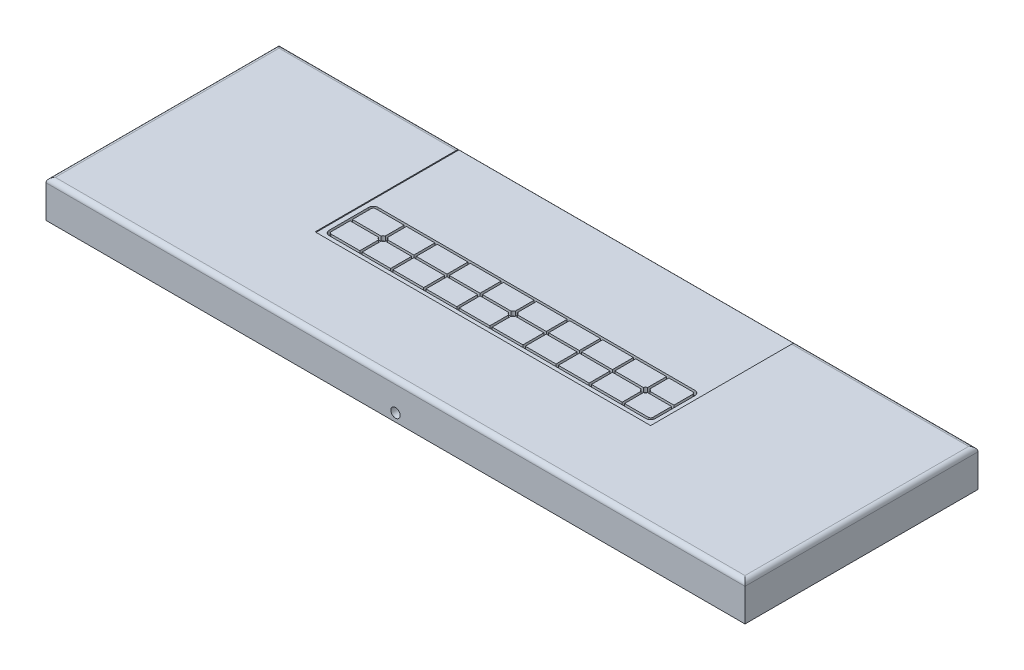
SolidWorks part; units mm, degrees
ref_plane "Front Plane" through (0, 0, 0) normal (0, 0, 1) x (1, 0, 0)
ref_plane "Top Plane" through (0, 0, 0) normal (0, 1, 0) x (1, 0, 0)
ref_plane "Right Plane" through (0, 0, 0) normal (1, 0, 0) x (0, 0, -1)
sketch "Sketch1" plane through (0, 0, 0) normal (0, 1, 0) x (1, 0, 0)
  line L1 (-750, 250) -> (750, 250)
  line L2 (-750, 250) -> (-750, -250)
  line L3 (-750, -250) -> (750, -250)
  line L4 (750, 250) -> (750, -250)
  line L5 (-750, 250) -> (750, -250) construction
  line L6 (-750, -250) -> (750, 250) construction
  point P0 (0, 0)
  dimension "D1" = 1500
  dimension "D2" = 500
extrude "Boss-Extrude1" add sketch "Sketch1" along normal blind 80
fillet "Fillet2" radius 10 4 edges at (0, 80, 250) (-750, 80, 0) (0, 80, -250) (750, 80, 0)
sketch "Sketch3" plane through (0, 0, 0) normal (0, 1, 0) x (1, 0, 0)
  line L0 (740, 148.17) -> (-740, 148.17) construction
  line L3 (-740, -148.17) -> (740, -148.17) construction
  line L4 (740, 240) -> (-740, 240) construction
  line L5 (623.2796, 240) -> (623.2796, -240) construction
  line L6 (-740, -240) -> (740, -240) construction
  dimension "D1" = 296.34
  dimension "D2" = 91.83
  dimension "D3" = 116.7204
sketch "Sketch6" plane through (0, 0, 0) normal (0, 1, 0) x (1, 0, 0)
  line L0 (623.88, 240) -> (623.88, -240) construction
  line L1 (-360, 62.5) -> (360, 62.5)
  line L2 (-360, 62.5) -> (-360, -62.5)
  line L3 (-360, -62.5) -> (360, -62.5)
  line L4 (360, 62.5) -> (360, -62.5)
  line L5 (-360, 62.5) -> (360, -62.5) construction
  line L6 (-360, -62.5) -> (360, 62.5) construction
  line L7 (740, 240) -> (-740, 240) construction
  line L8 (-740, -240) -> (740, -240) construction
  line L9 (740, -240) -> (740, 240) construction
  line L10 (-740, 148.68) -> (740, 148.68) construction
  line L11 (-740, 240) -> (-740, -240) construction
  point P0 (0, 0)
  dimension "D1" = 720
  dimension "D2" = 125
  dimension "D3" = 116.12
  dimension "D4" = 91.32
sketch "Sketch7" plane through (0, 0, 0) normal (0, 1, 0) x (1, 0, 0)
  line L1 (-661.88, 148.17) -> (473.88, 148.17) construction
  line L2 (-661.88, 148.17) -> (-661.88, -148.17) construction
  line L3 (-661.88, -148.17) -> (473.88, -148.17) construction
  line L4 (473.88, 148.17) -> (473.88, -148.17) construction
  line L5 (-661.88, 148.17) -> (473.88, -148.17) construction
  line L6 (-661.88, -148.17) -> (473.88, 148.17) construction
  line L7 (-740, 240) -> (-740, -240) construction
  line L8 (740, -240) -> (740, 240) construction
  line L9 (-661.88, 148.17) -> (-661.88, 308.5509) construction
  line L11 (473.88, 308.5509) -> (473.88, 148.17) construction
  line L12 (-360, -62.5) -> (-360, 376.5169)
  line L13 (360, -62.5) -> (360, 376.5169)
  line L14 (360, 376.5169) -> (-360, 376.5169)
  line L15 (-360, -62.5) -> (360, -62.5)
  point P8 (-94, 0)
  point P9 (-94, 0)
  point P10 (-516.2518, -356.0556)
  dimension "D1" = 78.12
  dimension "D2" = 266.12
  dimension "D3" = 296.34
extrude "Cut-Extrude2" cut sketch "Sketch7" against normal blind 2 from surface at 80 starting at face at (0, 80, 0)
sketch "Sketch5" plane through (0, 0, 0) normal (0, 1, 0) x (1, 0, 0)
  line L0 (-360, 62.5) -> (360, -62.5) construction
  line L6 (-340, 52.5) -> (340, 52.5)
  line L11 (-350, 42.5) -> (-350, -42.5)
  line L12 (-340, -52.5) -> (340, -52.5)
  line L17 (350, 42.5) -> (350, -42.5)
  line L18 (-360, 62.5) -> (-360, -62.5) construction
  line L19 (-360, -62.5) -> (360, -62.5) construction
  line L20 (360, 62.5) -> (360, -62.5) construction
  line L21 (-360, 62.5) -> (360, 62.5) construction
  line L22 (-360, -62.5) -> (360, 62.5) construction
  line L23 (-340, 47.5) -> (-279, 47.5)
  line L24 (-345, 42.5) -> (-345, 2.5)
  line L25 (-340, -47.5) -> (-279, -47.5)
  line L26 (345, 42.5) -> (345, 2.5)
  line L27 (2.5, -52.5) -> (2.5, -18.1303) construction
  line L28 (-350, 0) -> (350, 0) construction
  line L29 (-142, -2.5) -> (-142, -47.5)
  line L30 (0, 47.5) -> (0, 7.0711)
  line L31 (5, 47.5) -> (5, 7.0711)
  line L32 (-71, 47.5) -> (-71, 2.5)
  line L33 (-66, 47.5) -> (-66, 2.5)
  line L34 (142, 47.5) -> (142, 2.5)
  line L35 (147, 47.5) -> (147, 2.5)
  line L36 (71, 47.5) -> (71, 2.5)
  line L37 (76, 47.5) -> (76, 2.5)
  line L38 (213, 47.5) -> (213, 2.5)
  line L39 (218, 47.5) -> (218, 2.5)
  line L40 (284, 47.5) -> (284, 7.0711)
  line L41 (289, 47.5) -> (289, 7.0711)
  line L42 (-142, 47.5) -> (-142, 2.5)
  line L43 (-137, 47.5) -> (-137, 2.5)
  line L44 (-213, 47.5) -> (-213, 2.5)
  line L45 (-208, 47.5) -> (-208, 2.5)
  line L46 (-279, 47.5) -> (-279, 7.0711)
  line L47 (-274, 47.5) -> (-274, 7.0711)
  line L48 (-345, -2.5) -> (-283.5711, -2.5)
  line L49 (-345, 2.5) -> (-283.5711, 2.5)
  line L50 (-279, -7.0711) -> (-279, -47.5)
  line L51 (-274, -7.0711) -> (-274, -47.5)
  line L52 (-137, -2.5) -> (-71, -2.5)
  line L53 (-269.4289, -2.5) -> (-213, -2.5)
  line L54 (-269.4289, 2.5) -> (-213, 2.5)
  line L55 (-213, -2.5) -> (-213, -47.5)
  line L56 (-208, -2.5) -> (-208, -47.5)
  line L57 (-208, -2.5) -> (-142, -2.5)
  line L58 (-137, 2.5) -> (-71, 2.5)
  line L59 (-137, -2.5) -> (-137, -47.5)
  line L60 (-208, 2.5) -> (-142, 2.5)
  line L61 (-66, -2.5) -> (-4.5711, -2.5)
  line L62 (-66, 2.5) -> (-4.5711, 2.5)
  line L63 (-66, -2.5) -> (-66, -47.5)
  line L64 (-71, -2.5) -> (-71, -47.5)
  line L65 (0, -7.0711) -> (0, -47.5)
  line L66 (5, -7.0711) -> (5, -47.5)
  line L67 (9.5711, 2.5) -> (71, 2.5)
  line L68 (9.5711, -2.5) -> (71, -2.5)
  line L69 (76, -2.5) -> (142, -2.5)
  line L70 (76, -2.5) -> (76, -47.5)
  line L71 (71, -2.5) -> (71, -47.5)
  line L72 (76, 2.5) -> (142, 2.5)
  line L73 (142, -2.5) -> (142, -47.5)
  line L74 (147, -2.5) -> (147, -47.5)
  line L75 (147, -2.5) -> (213, -2.5)
  line L76 (147, 2.5) -> (213, 2.5)
  line L77 (213, -2.5) -> (213, -47.5)
  line L78 (218, -2.5) -> (218, -47.5)
  line L79 (218, 2.5) -> (279.4289, 2.5)
  line L80 (218, -2.5) -> (279.4289, -2.5)
  line L81 (284, -7.0711) -> (284, -47.5)
  line L82 (289, -7.0711) -> (289, -47.5)
  line L83 (293.5711, -2.5) -> (345, -2.5)
  line L84 (293.5711, 2.5) -> (345, 2.5)
  line L85 (345, -2.5) -> (345, -42.5)
  line L86 (-345, -2.5) -> (-345, -42.5)
  line L87 (-208, 47.5) -> (-142, 47.5)
  line L88 (-360, 84.24) -> (360, 84.24) construction
  line L89 (289, 47.5) -> (340, 47.5)
  line L90 (218, 47.5) -> (284, 47.5)
  line L91 (76, 47.5) -> (142, 47.5)
  line L92 (147, 47.5) -> (213, 47.5)
  line L93 (-66, 47.5) -> (0, 47.5)
  line L94 (5, 47.5) -> (71, 47.5)
  line L95 (-137, 47.5) -> (-71, 47.5)
  line L96 (-274, 47.5) -> (-213, 47.5)
  line L97 (-274, -47.5) -> (-213, -47.5)
  line L98 (-208, -47.5) -> (-142, -47.5)
  line L99 (-137, -47.5) -> (-71, -47.5)
  line L100 (-66, -47.5) -> (0, -47.5)
  line L101 (5, -47.5) -> (71, -47.5)
  line L102 (76, -47.5) -> (142, -47.5)
  line L103 (147, -47.5) -> (213, -47.5)
  line L104 (218, -47.5) -> (284, -47.5)
  line L105 (289, -47.5) -> (340, -47.5)
  line L106 (-279, 7.0711) -> (-274, -7.0711) construction
  line L107 (-274, 7.0711) -> (-279, -7.0711) construction
  line L108 (-360, -62.5) -> (-360, 246) construction
  line L109 (360, 246) -> (360, -62.5) construction
  line L110 (-740, 148.68) -> (740, 148.68) construction
  arc A0 (-340, -52.5) -> (-350, -42.5) centre (-340, -42.5) cw
  arc A1 (-350, 42.5) -> (-340, 52.5) centre (-340, 42.5) cw
  arc A2 (340, -52.5) -> (350, -42.5) centre (340, -42.5) ccw
  arc A3 (350, 42.5) -> (340, 52.5) centre (340, 42.5) ccw
  arc A4 (340, -47.5) -> (345, -42.5) centre (340, -42.5) ccw
  arc A5 (340, 47.5) -> (345, 42.5) centre (340, 42.5) cw
  arc A6 (-345, 42.5) -> (-340, 47.5) centre (-340, 42.5) cw
  arc A7 (-345, -42.5) -> (-340, -47.5) centre (-340, -42.5) ccw
  arc A8 (-279, 7.0711) -> (-283.5711, 2.5) centre (-276.5, 0) ccw
  arc A9 (0, 7.0711) -> (-4.5711, 2.5) centre (2.5, 0) ccw
  arc A10 (284, 7.0711) -> (279.4289, 2.5) centre (286.5, 0) ccw
  arc A11 (-283.5711, -2.5) -> (-279, -7.0711) centre (-276.5, 0) ccw
  arc A12 (-269.4289, 2.5) -> (-274, 7.0711) centre (-276.5, 0) ccw
  arc A13 (-274, -7.0711) -> (-269.4289, -2.5) centre (-276.5, 0) ccw
  arc A14 (9.5711, 2.5) -> (5, 7.0711) centre (2.5, 0) ccw
  arc A15 (-4.5711, -2.5) -> (0, -7.0711) centre (2.5, 0) ccw
  arc A16 (5, -7.0711) -> (9.5711, -2.5) centre (2.5, 0) ccw
  arc A17 (279.4289, -2.5) -> (284, -7.0711) centre (286.5, 0) ccw
  arc A18 (289, -7.0711) -> (293.5711, -2.5) centre (286.5, 0) ccw
  arc A19 (293.5711, 2.5) -> (289, 7.0711) centre (286.5, 0) ccw
  point P0 (0, 0)
  point P16 (0, 0)
  point P120 (286.5, -47.5)
  dimension "D5" = 5
  dimension "D6" = 5
  dimension "D7" = 10
  dimension "D8" = 5
  dimension "D30" = 15
  dimension "D33" = 7.5
  dimension "D34" = 15
  dimension "D1" = 10
  dimension "D2" = 10
  dimension "D3" = 10
  dimension "D4" = 10
  dimension "D9" = 5
  dimension "D10" = 5
  dimension "D11" = 5
  dimension "D12" = 5
  dimension "D13" = 5
  dimension "D14" = 5
  dimension "D15" = 5
  dimension "D16" = 5
  dimension "D17" = 66
  dimension "D18" = 66
  dimension "D19" = 66
  dimension "D20" = 5
  dimension "D21" = 66
  dimension "D22" = 66
  dimension "D23" = 66
  dimension "D24" = 66
  dimension "D25" = 66
  dimension "D26" = 66
  dimension "D27" = 2.5
  dimension "D28" = 2.5
  dimension "D29" = 5
  dimension "D31" = 2.5
  dimension "D32" = 5
  dimension "D35" = 2.5
  dimension "D36" = 64.44
extrude "Cut-Extrude1" cut sketch "Sketch5" against normal blind 10 from surface at 78 starting at face at (0, 78, -91.75)
sketch "Sketch8" plane through (0, 0, 0) normal (0, 1, 0) x (1, 0, 0)
  line L0 (284, 7.0711) -> (289, -7.0711) construction
  circle A0 centre (-276.5, 0) radius 5
  circle A1 centre (2.5, 0) radius 5
  circle A2 centre (286.5, 0) radius 5
  dimension "D1" = 10
  dimension "D2" = 10
  dimension "D3" = 10
extrude "Cut-Extrude3" cut sketch "Sketch8" against normal through all from surface at 80 starting at face at (0, 80, -44.375)
sketch "Sketch9" plane through (0, 0, 0) normal (0, 0, 1) x (1, 0, 0)
  line L0 (-740, 0) -> (740, 0) construction
  line L1 (360, 0) -> (-360, 0)
  line L2 (360, 0) -> (360, 40)
  line L3 (360, 40) -> (-360, 40)
  line L4 (-360, 0) -> (-360, 40)
  dimension "D1" = 40
  dimension "D2" = 360
  dimension "D3" = 360
extrude "Cut-Extrude4" cut sketch "Sketch9" along normal blind 100 and the other way blind 100
sketch "Sketch11" plane through (0, 0, 0) normal (0, 0, 1) x (1, 0, 0)
  line L0 (0, 0) -> (0, 35) construction
  line L1 (-2250, 35) -> (750, 35) construction
  line L3 (750, 70) -> (750, 0) construction
  circle A0 centre (0, 17.5) radius 10
  point P7 (-750, 35)
  dimension "D1" = 20
extrude "Cut-Extrude5" cut sketch "Sketch11" along normal up to surface (250 mm away) up to face at (0, 35, 250)
